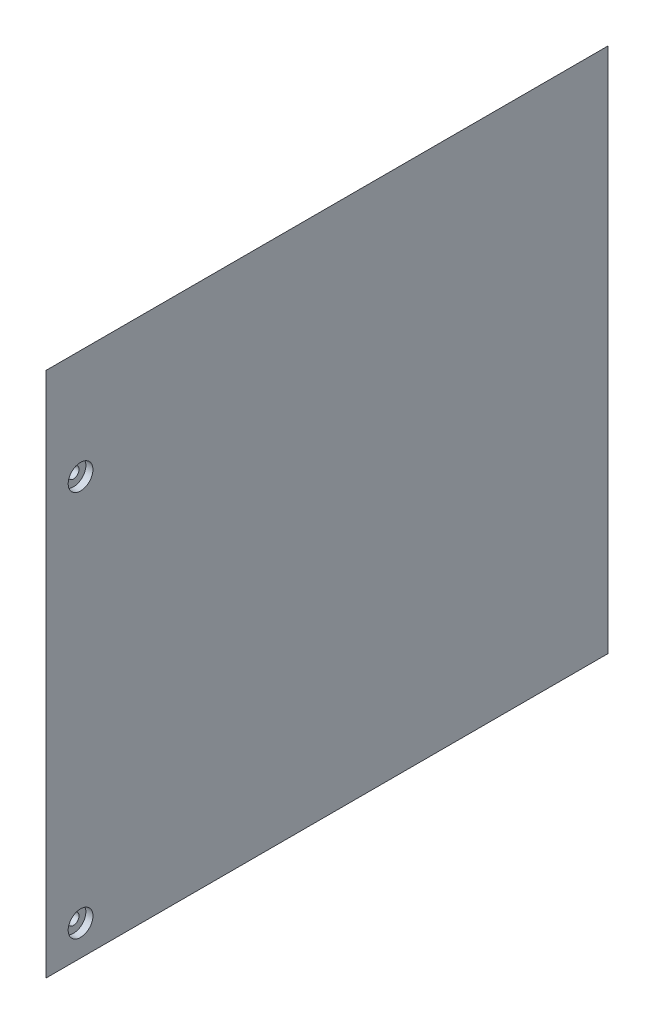
SolidWorks part; units mm, degrees
ref_plane "Front Plane" through (0, 0, 0) normal (0, 0, 1) x (1, 0, 0)
ref_plane "Top Plane" through (0, 0, 0) normal (0, 1, 0) x (1, 0, 0)
ref_plane "Right Plane" through (0, 0, 0) normal (1, 0, 0) x (0, 0, -1)
sketch "Sketch1" plane through (0, 0, 0) normal (1, 0, 0) x (0, 0, -1)
  line L1 (-150, 130) -> (150, 130)
  line L2 (-150, 130) -> (-150, -130)
  line L3 (-150, -130) -> (150, -130)
  line L4 (150, 130) -> (150, -130)
  point P4 (-150, 0)
  point P6 (0, 130)
  dimension "D1" = 300
  dimension "D2" = 260
extrude "Boss-Extrude1" add sketch "Sketch1" along normal blind 39
ref_plane "Plane3" through (0, 130, 0) normal (0, 1, 0) x (1, 0, 0)
ref_plane "Plane1" through (0, -130, 0) normal (0, -1, 0) x (-1, 0, 0)
ref_plane "Plane2" through (0, 0, -150) normal (0, 0, -1) x (-1, 0, 0)
sketch "Sketch3" plane through (0, -130, 0) normal (0, -1, 0) x (-1, 0, 0)
  line L0 (-39, 150) -> (0, 150)
  line L1 (0, -150) -> (0, 150) construction
  line L2 (-39, 150) -> (0, 150) construction
  line L3 (0, 150) -> (0, 111)
  line L4 (0, 111) -> (-39, 150)
  line L5 (0, -127.51) -> (0, -88.51)
  line L7 (0, -88.51) -> (-39, -127.51)
  line L9 (-39, -150) -> (-39, 150) construction
  line L13 (0, -127.51) -> (0, -150)
  line L14 (0, -150) -> (-39, -150)
  line L15 (-39, -127.51) -> (-39, -150)
  dimension "D1" = 45
  dimension "D2" = 45
  dimension "D3" = 39
  dimension "D4" = 22.49
extrude "Cut-Extrude1" cut sketch "Sketch3" against normal up to surface (260 mm away) up to face at (19.5, 130, 0)
sketch "Sketch5" plane through (0, 0, -150) normal (0, 0, -1) x (-1, 0, 0)
  line L4 (-39, 130) -> (0, 130)
  line L5 (0, 130) -> (0, 91)
  line L6 (0, 91) -> (-39, 130)
  line L7 (0, 130) -> (0, -130) construction
  dimension "D1" = 45
extrude "Cut-Extrude2" cut sketch "Sketch5" against normal blind 384
sketch "Sketch6" plane through (0, 0, 0) normal (1, 0, 0) x (0, 0, -1)
  line L0 (-88.51, -130) -> (-127.51, -130) construction
  line L1 (11.245, -130) -> (11.245, 130) construction
  line L2 (-88.51, -130) -> (111, -130) construction
  line L3 (150, 130) -> (-127.51, 130) construction
  circle A0 centre (-110.51, -115) radius 6
  circle A1 centre (-110.51, 76) radius 6
  circle A2 centre (133, 76) radius 6
  circle A3 centre (133, -115) radius 6
  dimension "D1" = 12
  dimension "D2" = 12
  dimension "D3" = 22
  dimension "D4" = 15
  dimension "D5" = 54
hole_wizard "Ø6.0mm Dowel Hole1" positions "Sketch7" profile "Sketch8" hole size "Ø6.0" standard "DIN"
sketch "Sketch7" plane through (0, 0, 0) normal (-1, 0, 0) x (0, 0, 1)
  point P0 (-133, -115)
  point P3 (-133, 76)
sketch "Sketch8" plane through (0, -115, -133) normal (0, 1, 0) x (0, 0, 1)
  line L0 (0, 0) -> (0, 31.8026)
  line L1 (0, 31.8026) -> (3, 30)
  line L2 (3, 30) -> (3, 0)
  line L5 (3, 0) -> (0, 0)
  line L10 (0, 31.8026) -> (-3, 30) construction
  line L11 (0, -6.35) -> (0, 107.95) construction
  dimension "Hole Dia." = 6
  dimension "Hole Depth" = 30
  dimension "Drill Angle" = 118
hole_wizard "CBORE for M5 Hex Head Bolt1" positions "Sketch9" profile "Sketch10" counterbore size "M5" standard "DIN"
sketch "Sketch9" plane through (39, 0, 0) normal (1, 0, 0) x (0, 0, -1)
  point P7 (-110.51, -115)
  point P10 (-110.51, 76)
sketch "Sketch10" plane through (39, -115, 110.51) normal (0, 1, 0) x (0, 0, -1)
  line L0 (0, 0) -> (0, 31.6524)
  line L1 (0, 31.6524) -> (2.75, 30)
  line L2 (2.75, 30) -> (2.75, 3.5)
  line L3 (2.75, 3.5) -> (6.119, 3.5)
  line L4 (6.119, 3.5) -> (6.119, 0)
  line L5 (6.119, 0) -> (0, 0)
  line L10 (0, 31.6524) -> (-2.75, 30) construction
  line L11 (0, -6.35) -> (0, 107.95) construction
  dimension "Hole Dia." = 5.5
  dimension "Hole Depth" = 30
  dimension "C'Bore Dia." = 12.238
  dimension "C'Bore Depth" = 3.5
  dimension "Drill Angle" = 118
sketch "Sketch11" plane through (0, 130, 0) normal (0, 1, 0) x (1, 0, 0)
  circle A0 centre (25, -95.51) radius 3
  circle A1 centre (25, 118) radius 3
  dimension "D1" = 6
  dimension "D2" = 6
  dimension "D3" = 25
  dimension "D4" = 32
  dimension "D5" = 32
  dimension "D6" = 25
hole_wizard "Ø6.0mm Dowel Hole2" positions "Sketch12" profile "Sketch13" hole size "Ø6.0" standard "DIN"
sketch "Sketch12" plane through (0, 130, 0) normal (0, 1, 0) x (1, 0, 0)
  point P0 (25, -95.51)
  point P3 (25, 118)
sketch "Sketch13" plane through (25, 130, 95.51) normal (1, 0, 0) x (0, 0, 1)
  line L0 (0, 0) -> (0, 31.8026)
  line L1 (0, 31.8026) -> (3, 30)
  line L2 (3, 30) -> (3, 0)
  line L5 (3, 0) -> (0, 0)
  line L10 (0, 31.8026) -> (-3, 30) construction
  line L11 (0, -6.35) -> (0, 107.95) construction
  dimension "Hole Dia." = 6
  dimension "Hole Depth" = 30
  dimension "Drill Angle" = 118
